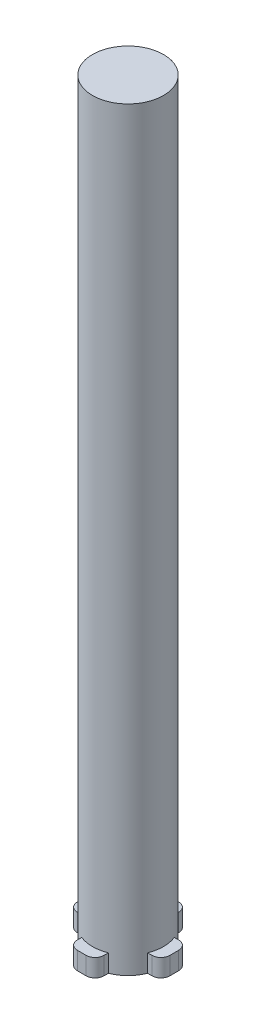
SolidWorks part; units mm, degrees
ref_plane "Alzado" through (0, 0, 0) normal (0, 0, 1) x (1, 0, 0)
ref_plane "Planta" through (0, 0, 0) normal (0, 1, 0) x (1, 0, 0)
ref_plane "Vista lateral" through (0, 0, 0) normal (1, 0, 0) x (0, 0, -1)
sketch "Croquis1" plane through (0, 0, 0) normal (0, 1, 0) x (1, 0, 0)
  circle A0 centre (0, 0) radius 4
  dimension "D1" = 8
extrude "Saliente-Extruir1" add sketch "Croquis1" along normal blind 85
sketch "Croquis2" plane through (0, 0, 0) normal (0, -1, 0) x (1, 0, 0)
  line L0 (0, 4) -> (0, 5.2081) construction
  line L1 (-1.5, 5.2081) -> (1.5, 5.2081)
  line L2 (-1.5, 5.2081) -> (-1.5, 3.7081)
  line L3 (1.5, 5.2081) -> (1.5, 3.7081)
  circle A0 centre (0, 0) radius 4 construction
  circle A2 centre (0, 0) radius 4
  arc A3 (1.5, 3.7081) -> (-1.5, 3.7081) centre (0, 0) ccw
  point P9 (0, 5.2081)
  dimension "D2" = 1.5
  dimension "D3" = 3
  dimension "D1" = 0
extrude "Saliente-Extruir2" add sketch "Croquis2" against normal blind 2 contours L2 A3 L3 L1
fillet "Redondeo1" radius 1 2 edges at (-1.5, 1, 5.2081) (1.5, 1, 5.2081)
pattern_circular "MatrizC1" count 4 over 360 about axis through (0, 0, 0) along (0, 1, 0) of "Redondeo1", "Saliente-Extruir2"
